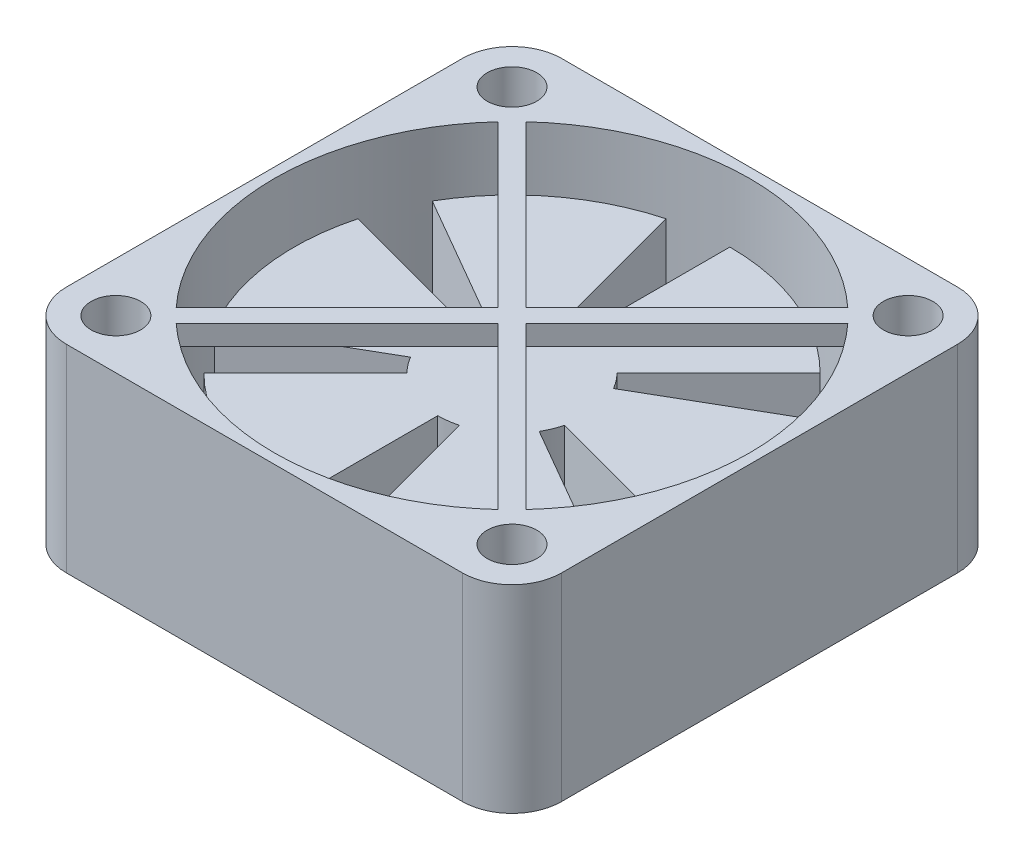
SolidWorks part; units mm, degrees
ref_plane "Front Plane" through (0, 0, 0) normal (0, 0, 1) x (1, 0, 0)
ref_plane "Top Plane" through (0, 0, 0) normal (0, 1, 0) x (1, 0, 0)
ref_plane "Right Plane" through (0, 0, 0) normal (1, 0, 0) x (0, 0, -1)
sketch "Sketch1" plane through (0, 0, 0) normal (0, 1, 0) x (1, 0, 0)
  line L1 (-25, -25) -> (25, -25)
  line L2 (-25, -25) -> (-25, 25)
  line L3 (-25, 25) -> (25, 25)
  line L4 (25, -25) -> (25, 25)
  line L5 (-25, -25) -> (25, 25) construction
  line L6 (-25, 25) -> (25, -25) construction
  line L7 (20, -20) -> (-20, -20) construction
  line L8 (20, -20) -> (20, 20) construction
  line L9 (20, 20) -> (-20, 20) construction
  line L10 (-20, -20) -> (-20, 20) construction
  line L11 (20, -20) -> (-20, 20) construction
  line L12 (20, 20) -> (-20, -20) construction
  circle A0 centre (-20, 20) radius 2.5
  circle A1 centre (20, 20) radius 2.5
  circle A2 centre (20, -20) radius 2.5
  circle A3 centre (-20, -20) radius 2.5
  point P0 (0, 0)
  point P6 (0, 0)
  dimension "D1" = 4
extrude "Boss-Extrude1" add sketch "Sketch1" along normal blind 20
sketch "Sketch2" plane through (0, 20, 0) normal (0, 1, 0) x (1, 0, 0)
  circle A1 centre (0, 0) radius 24
extrude "Cut-Extrude1" cut sketch "Sketch2" against normal blind 20
sketch "Sketch3" plane through (0, 0, 0) normal (0, 1, 0) x (1, 0, 0)
  line L0 (0, 7.5) -> (0, 22)
  line L1 (5.3033, 5.3033) -> (15.5563, 15.5563)
  line L2 (6.4952, 3.75) -> (19.0526, 11)
  line L3 (7.2444, -1.9411) -> (21.2504, -5.694)
  line L4 (6.4952, -3.75) -> (19.0526, -11)
  line L5 (1.9411, -7.2444) -> (5.694, -21.2504)
  line L6 (0, -7.5) -> (0, -22)
  line L7 (-5.3033, -5.3033) -> (-15.5563, -15.5563)
  line L8 (-6.4952, -3.75) -> (-19.0526, -11)
  line L9 (-7.2444, 1.9411) -> (-21.2504, 5.694)
  line L10 (-6.4952, 3.75) -> (-19.0526, 11)
  line L11 (-1.9411, 7.2444) -> (-5.694, 21.2504)
  arc A1 (15.5563, 15.5563) -> (0, 22) centre (0, 0) ccw
  arc A3 (21.2504, -5.694) -> (19.0526, 11) centre (0, 0) ccw
  arc A5 (5.694, -21.2504) -> (19.0526, -11) centre (0, 0) ccw
  arc A7 (-15.5563, -15.5563) -> (0, -22) centre (0, 0) ccw
  arc A9 (-21.2504, 5.694) -> (-19.0526, -11) centre (0, 0) ccw
  arc A11 (-5.694, 21.2504) -> (-19.0526, 11) centre (0, 0) ccw
  arc A12 (-6.4952, 3.75) -> (-7.2444, 1.9411) centre (0, 0) ccw
  arc A14 (0, 7.5) -> (-1.9411, 7.2444) centre (0, 0) ccw
  arc A15 (6.4952, 3.75) -> (5.3033, 5.3033) centre (0, 0) ccw
  arc A16 (6.4952, -3.75) -> (7.2444, -1.9411) centre (0, 0) ccw
  arc A17 (0, -7.5) -> (1.9411, -7.2444) centre (0, 0) ccw
  arc A18 (-6.4952, -3.75) -> (-5.3033, -5.3033) centre (0, 0) ccw
  dimension "D1" = 6
extrude "Boss-Extrude2" add sketch "Sketch3" along normal blind 10 from offset 5 separate body
sketch "Sketch4" plane through (0, 20, 0) normal (0, 1, 0) x (1, 0, 0)
  line L1 (0, 1.4142) -> (16.2487, 17.6629)
  line L2 (-17.6629, 16.2487) -> (-1.4142, 0)
  line L3 (-16.2487, -17.6629) -> (0, -1.4142)
  line L4 (-16.2487, 17.6629) -> (0, 1.4142)
  line L5 (-17.6629, -16.2487) -> (-1.4142, 0)
  line L9 (1.4142, 0) -> (17.6629, 16.2487)
  line L12 (0, -1.4142) -> (16.2487, -17.6629)
  line L14 (1.4142, 0) -> (17.6629, -16.2487)
  arc A0 (-17.6629, -16.2487) -> (-16.2487, -17.6629) centre (0, 0) ccw
  arc A1 (17.6629, 16.2487) -> (16.2487, 17.6629) centre (0, 0) ccw
  arc A2 (16.2487, -17.6629) -> (17.6629, -16.2487) centre (0, 0) ccw
  arc A3 (-17.6629, -16.2487) -> (-16.2487, -17.6629) centre (0, 0) ccw
  arc A4 (-16.2487, 17.6629) -> (-17.6629, 16.2487) centre (0, 0) ccw
  arc A5 (17.6629, 16.2487) -> (16.2487, 17.6629) centre (0, 0) ccw
  arc A6 (16.2487, -17.6629) -> (17.6629, -16.2487) centre (0, 0) ccw
  circle M2 centre (0, 0) radius 24
extrude "Boss-Extrude3" add sketch "Sketch4" against normal blind 2 contours L14 L9 L1 L4 L2 L5 L3 L12 M2
fillet "Fillet1" radius 5 4 edges at (25, 10, 25) (-25, 10, 25) (25, 10, -25) (-25, 10, -25)
